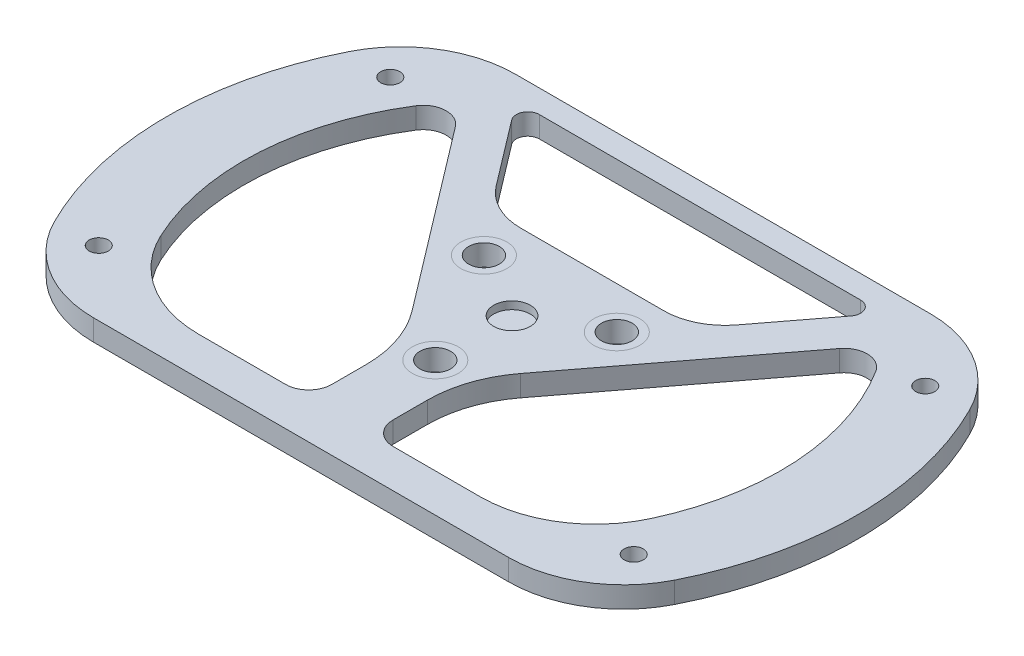
SolidWorks part; units mm, degrees
material "CF from CNC Madness"
ref_plane "Front Plane" through (0, 0, 0) normal (0, 0, 1) x (1, 0, 0)
ref_plane "Top Plane" through (0, 0, 0) normal (0, 1, 0) x (1, 0, 0)
ref_plane "Right Plane" through (0, 0, 0) normal (1, 0, 0) x (0, 0, -1)
sketch "Sketch1" plane through (0, 0, 0) normal (0, 1, 0) x (1, 0, 0)
  line L0 (-114.3, 0) -> (114.3, 0) construction
  line L1 (-88.8994, 69.85) -> (88.8994, 69.85)
  line L2 (0, 0) -> (0, 69.85) construction
  line L3 (-88.8994, -69.85) -> (88.8994, -69.85)
  line L25 (-60.8643, 62.23) -> (60.8643, 62.23)
  line L34 (-66.2189, -57.15) -> (-10.16, -57.15)
  line L38 (0, 0) -> (0, -25.4) construction
  line L46 (-10.16, -25.3621) -> (-10.16, -57.15)
  line L47 (10.16, -25.3621) -> (10.16, -57.15)
  line L48 (10.16, -57.15) -> (66.2189, -57.15)
  line L55 (-60.8643, 62.23) -> (-33.7307, 26.5783)
  line L56 (-33.7307, 26.5783) -> (33.7307, 26.5783)
  line L57 (33.7307, 26.5783) -> (60.8643, 62.23)
  line L58 (-69.8364, 53.0487) -> (-10.16, -25.3621)
  line L59 (69.8364, 53.0487) -> (10.16, -25.3621)
  arc A0 (-88.8994, 69.85) -> (-88.8994, -69.85) centre (-5.5584, 0) ccw
  arc A1 (88.8994, 69.85) -> (88.8994, -69.85) centre (5.5584, 0) cw
  arc A9 (-69.8364, 53.0487) -> (-88.9, 0) centre (-5.5584, 0) ccw
  arc A10 (-69.4325, 53.5344) -> (-69.4325, -53.5344) centre (-5.5584, 0) ccw construction
  arc A12 (-88.9, 0) -> (-66.2189, -57.15) centre (-5.5584, 0) ccw
  arc A13 (88.9, 0) -> (66.2189, -57.15) centre (5.5584, 0) cw
  arc A14 (69.8364, 53.0487) -> (88.9, 0) centre (5.5584, 0) cw
  circle A22 centre (0, 0) radius 25.4 construction
  circle A23 centre (0, -25.4) radius 5.08
  circle A26 centre (-21.997, 12.7) radius 5.08
  circle A27 centre (21.997, 12.7) radius 5.08
  circle A33 centre (-88.56, 48.26) radius 3.175
  circle A34 centre (-88.56, -48.26) radius 3.175
  circle A35 centre (88.56, -48.26) radius 3.175
  circle A36 centre (88.56, 48.26) radius 3.175
  point P10 (0, 69.85)
  point P29 (0, 0)
  point P47 (114.3, 0)
  point P50 (0, -69.85)
  point P54 (0, 0)
  dimension "D2" = 7.62
  dimension "D3" = 228.6
  dimension "D5" = 12.7
  dimension "D8" = 108.7416
  dimension "D11" = 12.7
  dimension "D12" = 50.8
  dimension "D13" = 10.16
  dimension "D17" = 6.35
  dimension "D4" = 20.32
  dimension "D7" = 139.7
  dimension "D10" = 25.4
  dimension "D14" = 3
  dimension "D18" = 48.26
  dimension "D19" = 96.012
extrude "Boss-Extrude1" add sketch "Sketch1" along normal blind 7
fillet "Fillet6" radius 38.1 6 edges at (-88.8994, 3.5, 69.85) (88.8994, 3.5, 69.85) (-88.8994, 3.5, -69.85) (88.8994, 3.5, -69.85) (66.2189, 3.5, 57.15) (-66.2189, 3.5, 57.15)
fillet "Fillet9" radius 7.62 2 edges at (-10.16, 3.5, 57.15) (10.16, 3.5, 57.15)
fillet "Fillet10" radius 7.62 2 edges at (69.8364, 3.5, -53.0487) (-69.8364, 3.5, -53.0487)
fillet "Fillet11" radius 3.81 2 edges at (60.8643, 3.5, -62.23) (-60.8643, 3.5, -62.23)
fillet "Fillet12" radius 20.32 2 edges at (-33.7307, 3.5, -26.5783) (33.7307, 3.5, -26.5783)
fillet "Fillet13" radius 38.1 2 edges at (10.16, 3.5, 25.3621) (-10.16, 3.5, 25.3621)
sketch "Sketch2" plane through (0, 7, 0) normal (0, 1, 0) x (1, 0, 0)
  circle A0 centre (0, 0) radius 6.0679
extrude "Cut-Extrude1" cut sketch "Sketch2" against normal blind 2.54 contours A0
sketch "Sketch3" plane through (0, 7, 0) normal (0, 1, 0) x (1, 0, 0)
  circle A0 centre (0, 0) radius 25.4 construction
  circle A1 centre (0, -25.4) radius 7.62
  circle A2 centre (-21.997, 12.7) radius 7.62
  circle A3 centre (21.997, 12.7) radius 7.62
  point P12 (0, 0)
  dimension "D1" = 50.8
  dimension "0.6" = 15.24
  dimension "D3" = 3
split line "Split Line1"
